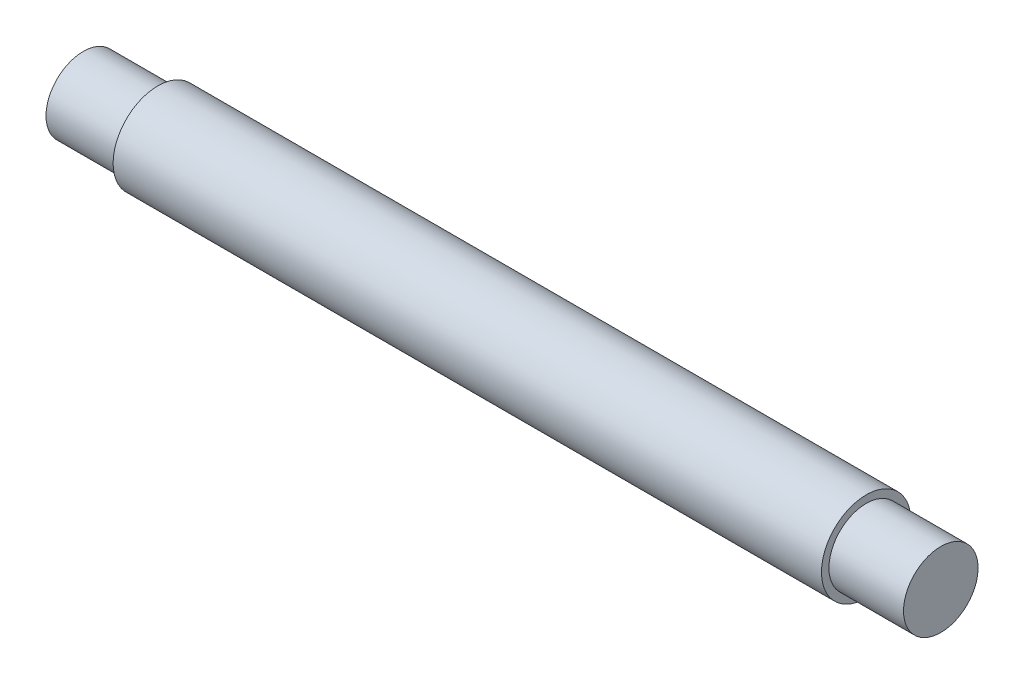
SolidWorks part; units mm, degrees
ref_plane "Front Plane" through (0, 0, 0) normal (0, 0, 1) x (1, 0, 0)
ref_plane "Top Plane" through (0, 0, 0) normal (0, 1, 0) x (1, 0, 0)
ref_plane "Right Plane" through (0, 0, 0) normal (1, 0, 0) x (0, 0, -1)
sketch "Sketch1" plane through (0, 0, 0) normal (0, 1, 0) x (1, 0, 0)
  line L0 (0, 0) -> (115, 0) construction
  line L1 (115, 0) -> (115, 5)
  line L2 (115, 5) -> (105, 5)
  line L3 (105, 5) -> (105, 6)
  line L4 (105, 6) -> (10, 6)
  line L5 (10, 6) -> (10, 5)
  line L6 (10, 5) -> (0, 5)
  line L7 (0, 5) -> (0, 0)
  line L8 (0, 0) -> (115, 0)
  dimension "D1" = 115
  dimension "D2" = 10
  dimension "D3" = 6
  dimension "D4" = 5
revolve "Revolve1" add sketch "Sketch1" angle 360 about L0
cosmetic thread "Cosmetic Thread1"
cosmetic thread "Cosmetic Thread2"
